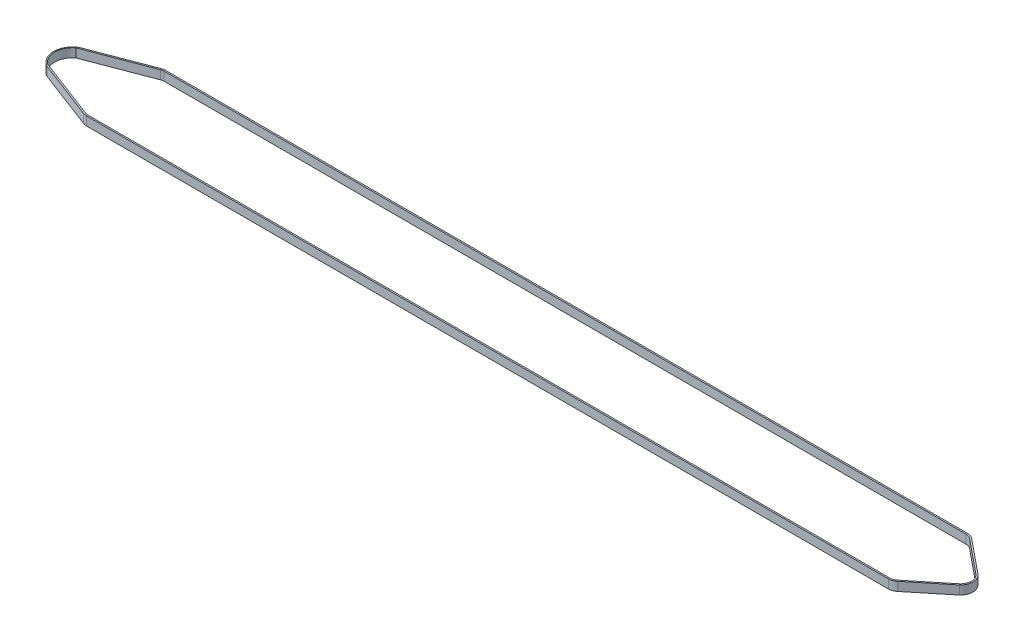
SolidWorks part; units mm, degrees
ref_plane "Płaszczyzna przednia" through (0, 0, 0) normal (0, 0, 1) x (1, 0, 0)
ref_plane "Płaszczyzna górna" through (0, 0, 0) normal (0, 1, 0) x (1, 0, 0)
ref_plane "Płaszczyzna prawa" through (0, 0, 0) normal (1, 0, 0) x (0, 0, -1)
sketch "Szkic1" plane through (0, 0, 0) normal (0, 1, 0) x (1, 0, 0)
  line L0 (-326.1638, 0) -> (341.3081, 0) construction
  line L1 (-274, -20) -> (274, -20)
  line L2 (-274, -20) -> (-274, 20)
  line L3 (-274, 20) -> (274, 20)
  line L4 (274, -20) -> (274, 20)
  line L5 (-274, -20) -> (274, 20) construction
  line L6 (-274, 20) -> (274, -20) construction
  line L7 (278.015, -24.4587) -> (301.2087, -5.5734)
  line L8 (274, -26) -> (-274, -26)
  line L9 (-318.0315, -9.6336) -> (-276.1375, -25.6063)
  line L10 (-276.4938, -26.5407) -> (-317.1999, -11.0209)
  line L11 (-274, -27) -> (274, -27)
  line L12 (278.6841, -25.2018) -> (301.8778, -6.3165)
  line L13 (278.6841, 25.2018) -> (301.8778, 6.3165)
  line L14 (278.015, 24.4587) -> (301.2087, 5.5734)
  line L15 (274, 26) -> (-274, 26)
  line L16 (-274, 27) -> (274, 27)
  line L17 (-318.0315, 9.6336) -> (-276.1375, 25.6063)
  line L18 (-276.4938, 26.5407) -> (-317.1999, 11.0209)
  arc A12 (-276.1375, 25.6063) -> (-274, 26) centre (-274, 20) cw
  arc A13 (-276.4938, 26.5407) -> (-274, 27) centre (-274, 20) cw
  arc A14 (-276.1375, -25.6063) -> (-274, -26) centre (-274, -20) ccw
  arc A15 (-276.4938, -26.5407) -> (-274, -27) centre (-274, -20) ccw
  arc A16 (274, -26) -> (278.015, -24.4587) centre (274, -20) ccw
  arc A17 (274, -27) -> (278.6841, -25.2018) centre (274, -20) ccw
  arc A18 (278.015, 24.4587) -> (274, 26) centre (274, 20) ccw
  arc A19 (278.6841, 25.2018) -> (274, 27) centre (274, 20) ccw
  arc A20 (301.2087, -5.5734) -> (301.2087, 5.5734) centre (296.19, 0) ccw
  arc A21 (301.8778, -6.3165) -> (301.8778, 6.3165) centre (296.19, 0) ccw
  arc A22 (-318.0315, 9.6336) -> (-318.0315, -9.6336) centre (-310.65, 0) ccw
  arc A23 (-317.1999, 11.0209) -> (-317.1999, -11.0209) centre (-310.65, 0) ccw
  point P0 (0, 0)
  point P23 (0, 0)
  dimension "D5" = 548
  dimension "D6" = 7.5
  dimension "D9" = 548
  dimension "D10" = 7
  dimension "D11" = 8.5
  dimension "D12" = 6
  dimension "D13" = 6
  dimension "D14" = 7
  dimension "D1" = 548
  dimension "D2" = 40
  dimension "D4" = 36.65
  dimension "D7" = 22.19
extrude "Dodanie-wyciągnięcie1" add sketch "Szkic1" along normal blind 6 contours L18 A23 L10 A15 L11 A17 L12 A21 L13 A19 L16 A13 A22 L17 A12 L15 A18 L14 A20 L7 A16 L8 A14 L9
